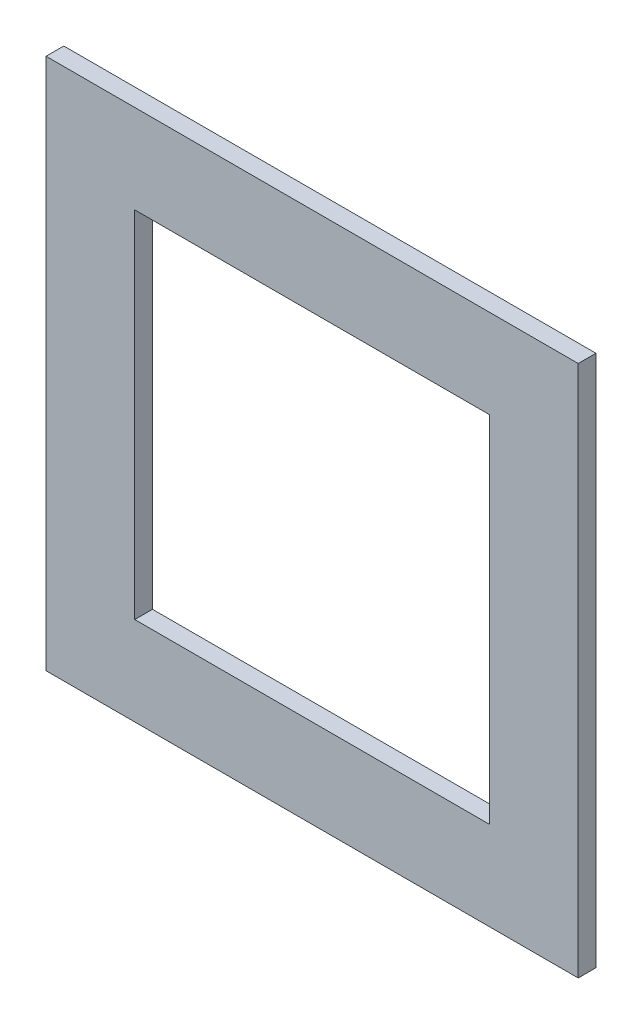
SolidWorks part; units mm, degrees
ref_plane "Front Plane" through (0, 0, 0) normal (0, 0, 1) x (1, 0, 0)
ref_plane "Top Plane" through (0, 0, 0) normal (0, 1, 0) x (1, 0, 0)
ref_plane "Right Plane" through (0, 0, 0) normal (1, 0, 0) x (0, 0, -1)
sketch "Sketch1" plane through (0, 0, 0) normal (0, 0, 1) x (1, 0, 0)
  line L1 (-150, -150) -> (150, -150)
  line L2 (-150, -150) -> (-150, 150)
  line L3 (-150, 150) -> (150, 150)
  line L4 (150, -150) -> (150, 150)
  line L5 (-150, -150) -> (150, 150) construction
  line L6 (-150, 150) -> (150, -150) construction
  line L7 (-100, -100) -> (100, -100)
  line L8 (-100, -100) -> (-100, 100)
  line L9 (-100, 100) -> (100, 100)
  line L10 (100, -100) -> (100, 100)
  line L11 (-100, -100) -> (100, 100) construction
  line L12 (-100, 100) -> (100, -100) construction
  point P0 (0, 0)
  point P5 (0, 0)
  dimension "D1" = 200
  dimension "D3" = 50
extrude "Boss-Extrude1" add sketch "Sketch1" along normal blind 10
